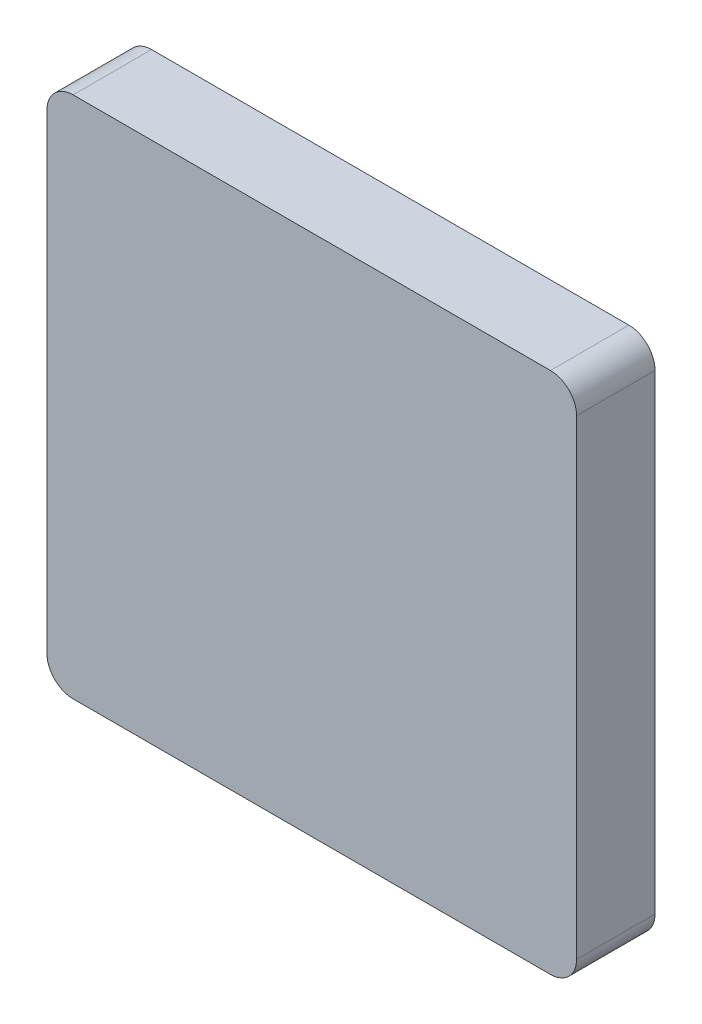
SolidWorks part; units mm, degrees
ref_plane "Front Plane" through (0, 0, 0) normal (0, 0, 1) x (1, 0, 0)
ref_plane "Top Plane" through (0, 0, 0) normal (0, 1, 0) x (1, 0, 0)
ref_plane "Right Plane" through (0, 0, 0) normal (1, 0, 0) x (0, 0, -1)
sketch "Sketch1" plane through (0, 0, 0) normal (0, 0, 1) x (1, 0, 0)
  line L1 (-20.25, 20) -> (20.25, 20)
  line L2 (-20.25, 20) -> (-20.25, -20)
  line L3 (-20.25, -20) -> (20.25, -20)
  line L4 (20.25, 20) -> (20.25, -20)
  line L5 (-20.25, 20) -> (20.25, -20) construction
  line L6 (-20.25, -20) -> (20.25, 20) construction
  point P0 (0, 0)
  dimension "D1" = 40.5
  dimension "D2" = 40
extrude "Boss-Extrude1" add sketch "Sketch1" along normal blind 6
fillet "Fillet1" radius 2 4 edges at (-20.25, -20, 3) (20.25, -20, 3) (20.25, 20, 3) (-20.25, 20, 3)
